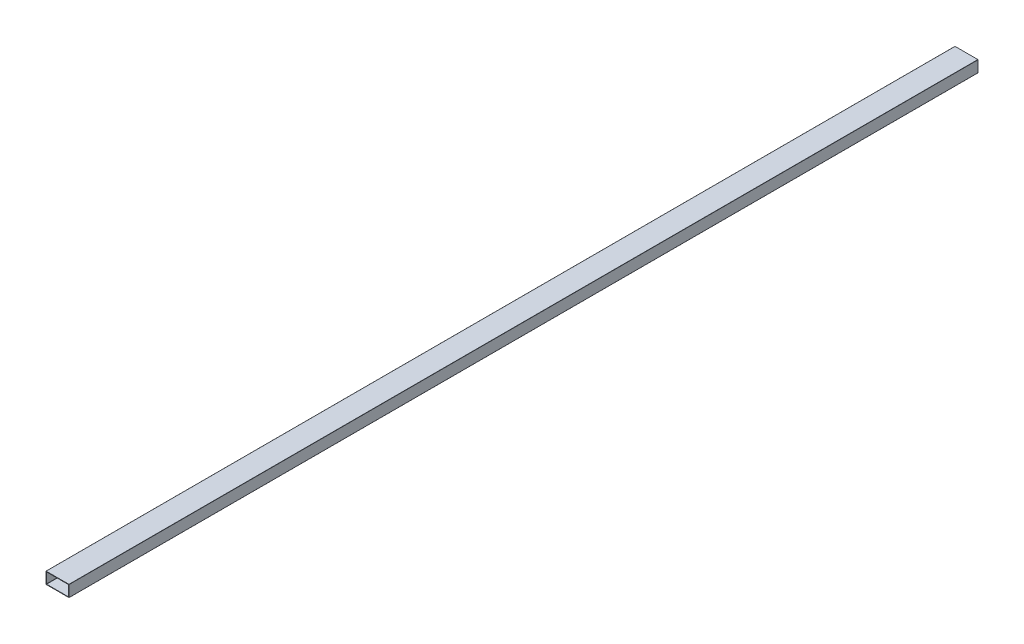
SolidWorks part; units mm, degrees
material "AISI 1035 Acero (SS)"
ref_plane "Alzado" through (0, 0, 0) normal (0, 0, 1) x (1, 0, 0)
ref_plane "Planta" through (0, 0, 0) normal (0, 1, 0) x (1, 0, 0)
ref_plane "Vista lateral" through (0, 0, 0) normal (1, 0, 0) x (0, 0, -1)
sketch "Croquis1" plane through (0, 0, 0) normal (0, 0, 1) x (1, 0, 0)
  line L0 (-73.16, -35.06) -> (-73.16, 35.06)
  line L1 (-76.2, -38.1) -> (76.2, -38.1)
  line L2 (-76.2, -38.1) -> (-76.2, 38.1)
  line L3 (-76.2, 38.1) -> (76.2, 38.1)
  line L4 (76.2, -38.1) -> (76.2, 38.1)
  line L5 (-76.2, -38.1) -> (76.2, 38.1) construction
  line L6 (-76.2, 38.1) -> (76.2, -38.1) construction
  line L7 (-73.16, 35.06) -> (73.16, 35.06)
  line L8 (73.16, -35.06) -> (73.16, 35.06)
  line L9 (-73.16, -35.06) -> (73.16, -35.06)
  point P0 (0, 0)
  dimension "D1" = 76.2
  dimension "D2" = 152.4
  dimension "D3" = 3.04
extrude "Saliente-Extruir1" add sketch "Croquis1" against normal blind 6000
fillet "Redondeo1" radius 1 8 edges at (-73.16, 35.06, -3000) (73.16, 35.06, -3000) (73.16, -35.06, -3000) (-76.2, -38.1, -3000) (-76.2, 38.1, -3000) (-73.16, -35.06, -3000) (76.2, -38.1, -3000) (76.2, 38.1, -3000)
